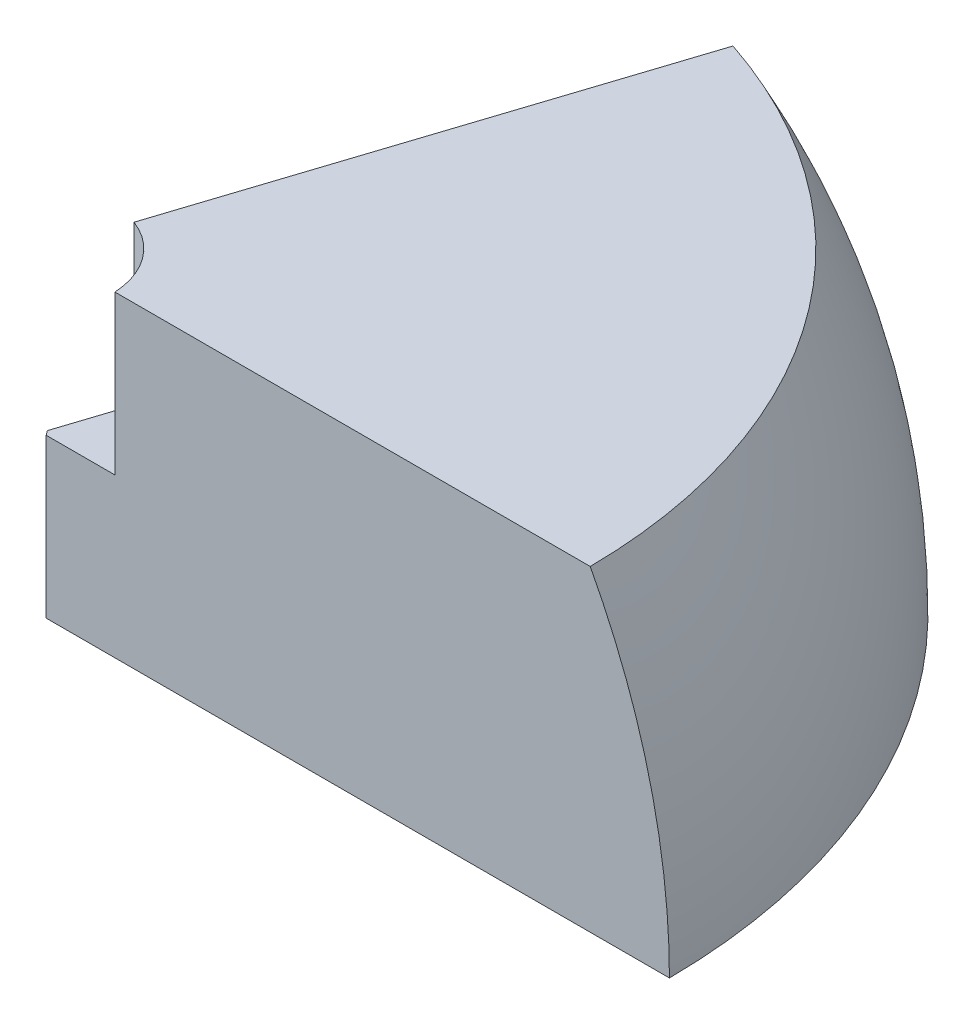
SolidWorks part; units mm, degrees
material "Polyurethane Foam Rigid"
ref_plane "Front Plane" through (0, 0, 0) normal (0, 0, 1) x (1, 0, 0)
ref_plane "Top Plane" through (0, 0, 0) normal (0, 1, 0) x (1, 0, 0)
ref_plane "Right Plane" through (0, 0, 0) normal (1, 0, 0) x (0, 0, -1)
sketch "Sketch1" plane through (0, 0, 0) normal (0, 0, 1) x (1, 0, 0)
  line L0 (0, 0) -> (0, 50.8)
  line L1 (0, 50.8) -> (88.9, 50.8)
  line L2 (0, 0) -> (101.6, 0)
  line L3 (101.6, 0) -> (101.6, -59.9199) construction
  arc A0 (88.9, 50.8) -> (101.6, 0) centre (-6.35, 0) cw
  dimension "D1" = 101.6
  dimension "D2" = 50.8
  dimension "D3" = 12.7
revolve "Revolve1" add sketch "Sketch1" angle 72 about L0
sketch "Sketch3" plane through (0, 0, 0) normal (-0.9511, 0, -0.309) x (-0.309, 0, 0.9511)
  line L7 (0, 50.8) -> (-88.9, 50.8)
  line L9 (-101.6, 0) -> (0, 0)
  line L10 (0, 0) -> (0, 50.8)
  line L13 (0, 50.8) -> (-88.9, 50.8)
  line L15 (-101.6, 0) -> (0, 0)
  line L16 (0, 0) -> (0, 50.8)
  arc A1 (-88.9, 50.8) -> (-101.6, 0) centre (6.35, 0) ccw
  arc A2 (-88.9, 50.8) -> (-101.6, 0) centre (6.35, 0) ccw
  dimension "D1" = 0
extrude "Cut-Extrude2" cut sketch "Sketch3" against normal blind 0.635
sketch "Sketch4" plane through (0, 0, 0) normal (0, 0, 1) x (1, 0, 0)
  line L6 (0.6677, 50.8) -> (0.6677, 0)
  line L7 (0.6677, 0) -> (101.6, 0)
  line L9 (88.9, 50.8) -> (0.6677, 50.8)
  line L12 (0.6677, 50.8) -> (0.6677, 0)
  line L13 (0.6677, 0) -> (101.6, 0)
  line L15 (88.9, 50.8) -> (0.6677, 50.8)
  arc A1 (101.6, 0) -> (88.9, 50.8) centre (-6.35, 0) ccw
  arc A2 (101.6, 0) -> (88.9, 50.8) centre (-6.35, 0) ccw
  dimension "D1" = 0
extrude "Cut-Extrude3" cut sketch "Sketch4" against normal blind 0.635
sketch "Sketch2" plane through (0, 50.8, 0) normal (0, 1, 0) x (1, 0, 0)
  circle A0 centre (0, 0) radius 12.7
  dimension "D1" = 25.4
extrude "Cut-Extrude1" cut sketch "Sketch2" against normal blind 25.4
sketch "Sketch5" plane through (0, 25.4, 0) normal (0, 1, 0) x (1, 0, 0)
  line L0 (1.6589, 0.635) -> (1.1166, 1.3815)
  line L1 (12.6841, 0.635) -> (0.874, 0.635) construction
  line L2 (0.874, 0.635) -> (4.5235, 11.8671) construction
  line L3 (1.1166, 1.3815) -> (0.874, 0.635)
  line L4 (0.874, 0.635) -> (1.6589, 0.635)
  dimension "D1" = 0.635
extrude "Cut-Extrude4" cut sketch "Sketch5" against normal up to next
